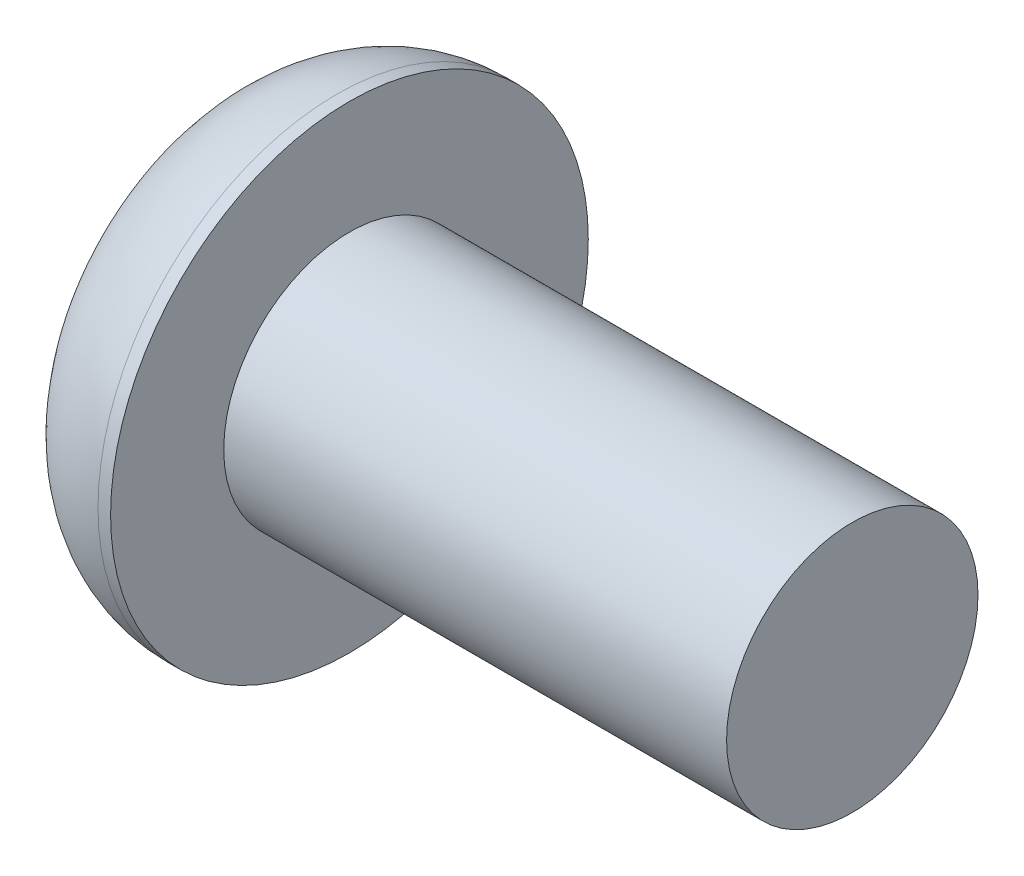
SolidWorks part; units mm, degrees
material "AISI 1020"
ref_plane "Front Plane" through (0, 0, 0) normal (0, 0, 1) x (1, 0, 0)
ref_plane "Top Plane" through (0, 0, 0) normal (0, 1, 0) x (1, 0, 0)
ref_plane "Right Plane" through (0, 0, 0) normal (1, 0, 0) x (0, 0, -1)
sketch "Sketch1" plane through (0, 0, 0) normal (0, 1, 0) x (1, 0, 0)
  line L0 (0, 0) -> (7.65, 0)
  line L1 (7.65, 0) -> (7.65, 1.5)
  line L2 (7.65, 1.5) -> (1.65, 1.5)
  line L3 (1.65, 1.5) -> (1.65, 2.85)
  line L4 (1.65, 2.85) -> (1.5, 2.85)
  line L5 (0, 1.35) -> (0, 0)
  line L6 (0, 0) -> (-8.9321, 0) construction
  arc A0 (0, 1.35) -> (1.5, 2.85) centre (1.5, 1.35) cw
  point P11 (0, 2.85)
  dimension "D5" = 1.5
  dimension "D1" = 1.5
  dimension "D2" = 6
  dimension "D3" = 1.65
  dimension "D4" = 2.85
revolve "Revolve1" add sketch "Sketch1" angle 360 about L6
sketch "Sketch2" plane through (0, 0, 0) normal (-1, 0, 0) x (0, 0, 1)
  line L1 (1.1547, 0) -> (0.5774, 1)
  line L2 (0.5774, 1) -> (-0.5774, 1)
  line L3 (-0.5774, 1) -> (-1.1547, 0)
  line L4 (-1.1547, 0) -> (-0.5774, -1)
  line L5 (-0.5774, -1) -> (0.5774, -1)
  line L6 (0.5774, -1) -> (1.1547, 0)
  circle A0 centre (0, 0) radius 1 construction
  dimension "D1" = 2
extrude "Cut-Extrude1" cut sketch "Sketch2" against normal blind 1.04
